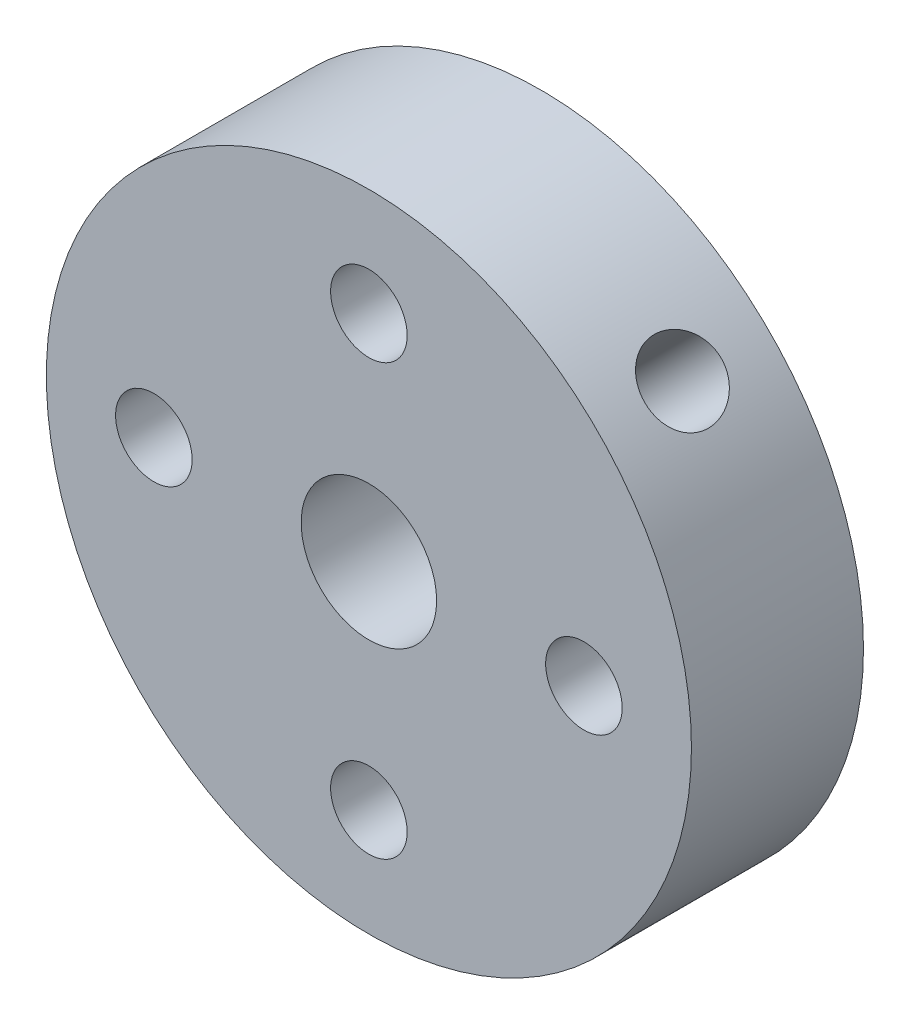
SolidWorks part; units mm, degrees
ref_plane "Front Plane" through (0, 0, 0) normal (0, 0, 1) x (1, 0, 0)
ref_plane "Top Plane" through (0, 0, 0) normal (0, 1, 0) x (1, 0, 0)
ref_plane "Right Plane" through (0, 0, 0) normal (1, 0, 0) x (0, 0, -1)
sketch "Sketch1" plane through (0, 0, 0) normal (0, 0, 1) x (1, 0, 0)
  line L0 (0, 0) -> (6.7352, 6.7352) construction
  line L1 (6.7352, 6.7352) -> (6.35, 0) construction
  line L2 (6.35, 0) -> (6.7352, 6.7352) construction
  line L3 (6.7352, 6.7352) -> (0, 6.35) construction
  circle A0 centre (0, 0) radius 9.525
  circle A1 centre (0, 0) radius 2
  circle A2 centre (-6.35, 0) radius 1.1303
  circle A3 centre (0, 6.35) radius 1.1303
  circle A4 centre (6.35, 0) radius 1.1303
  circle A5 centre (0, -6.35) radius 1.1303
  dimension "D1" = 19.05
  dimension "D2" = 4
  dimension "D4" = 2.2606
  dimension "D3" = 6.35
  dimension "D5" = 4
extrude "Boss-Extrude1" add sketch "Sketch1" along normal blind 5.08
ref_plane "Plane1" through (6.7352, 6.7352, 0) normal (0.7071, 0.7071, 0) x (-0.7071, 0.7071, 0)
sketch "Sketch2" plane through (6.7352, 6.7352, 0) normal (0.7071, 0.7071, 0) x (-0.7071, 0.7071, 0)
  circle A0 centre (0, 2.54) radius 1.1303
  dimension "D1" = 2.2606
  dimension "D2" = 2.54
extrude "Cut-Extrude1" cut sketch "Sketch2" against normal blind 10.16
